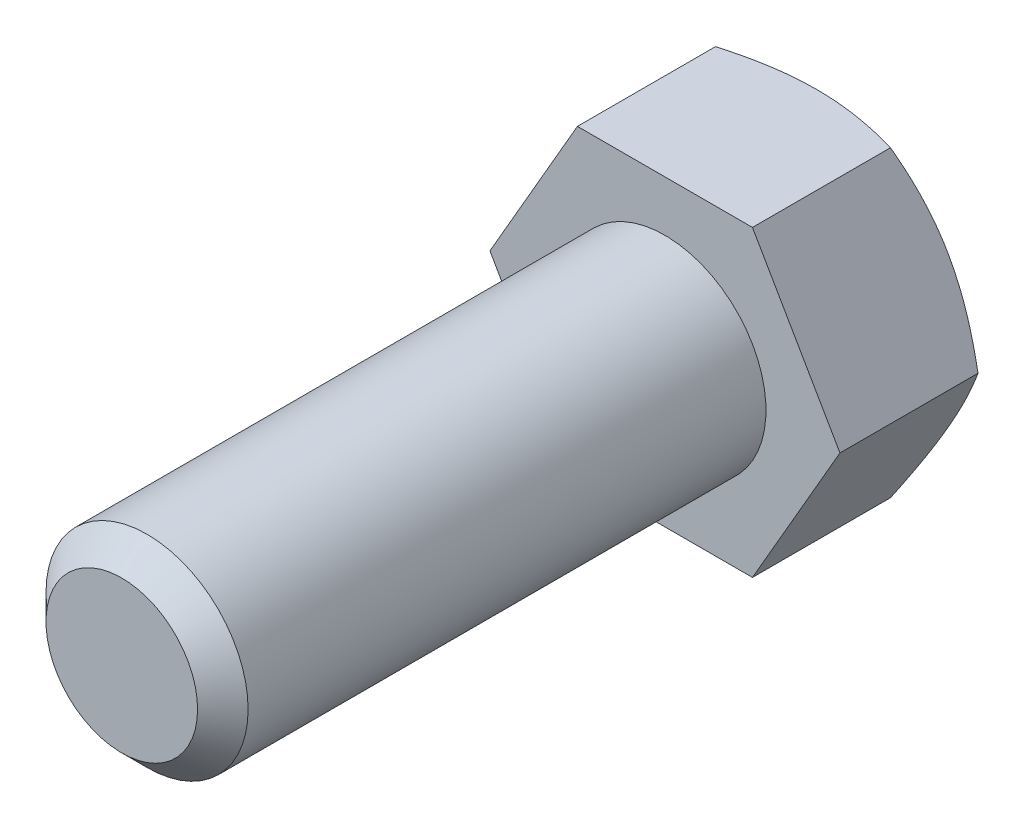
SolidWorks part; units mm, degrees
ref_plane "前基準面" through (0, 0, 0) normal (0, 0, 1) x (1, 0, 0)
ref_plane "上基準面" through (0, 0, 0) normal (0, 1, 0) x (1, 0, 0)
ref_plane "右基準面" through (0, 0, 0) normal (1, 0, 0) x (0, 0, -1)
sketch "草圖2" plane through (0, 0, 0) normal (0, 0, 1) x (1, 0, 0)
  circle A0 centre (0, 0) radius 4
  dimension "D1" = 8
extrude "伸長1" add sketch "草圖2" along normal blind 21.5
cosmetic thread "裝飾螺紋線1" parameters "D1"=17.5, "D2"=6
sketch "草圖3" plane through (0, 0, 0) normal (0, 0, -1) x (-1, 0, 0)
  line L1 (3.4641, -6) -> (6.9282, 0)
  line L2 (6.9282, 0) -> (3.4641, 6)
  line L3 (3.4641, 6) -> (-3.4641, 6)
  line L4 (-3.4641, 6) -> (-6.9282, 0)
  line L5 (-6.9282, 0) -> (-3.4641, -6)
  line L6 (-3.4641, -6) -> (3.4641, -6)
  circle A0 centre (0, 0) radius 6 construction
  dimension "D1" = 12
extrude "伸長2" add sketch "草圖3" along normal blind 6
sketch "草圖5" plane through (0, 0, 0) normal (0, 1, 0) x (1, 0, 0)
  line L0 (0, 0) -> (0, 7.3551) construction
  line L1 (6.9282, 5.4641) -> (6.9282, 6)
  line L2 (6.9282, 6) -> (6.9282, 0) construction
  line L3 (6.9282, 6) -> (6, 6)
  line L4 (3.4641, 6) -> (6.9282, 6) construction
  line L5 (6, 6) -> (6.9282, 5.4641)
  dimension "D1" = 60
  dimension "D2" = 12
revolve "除料-旋轉1" cut sketch "草圖5" angle 360 about L0
chamfer "導角1" distance 1 angle 45 1 edges at (4, 0, 21.5)
